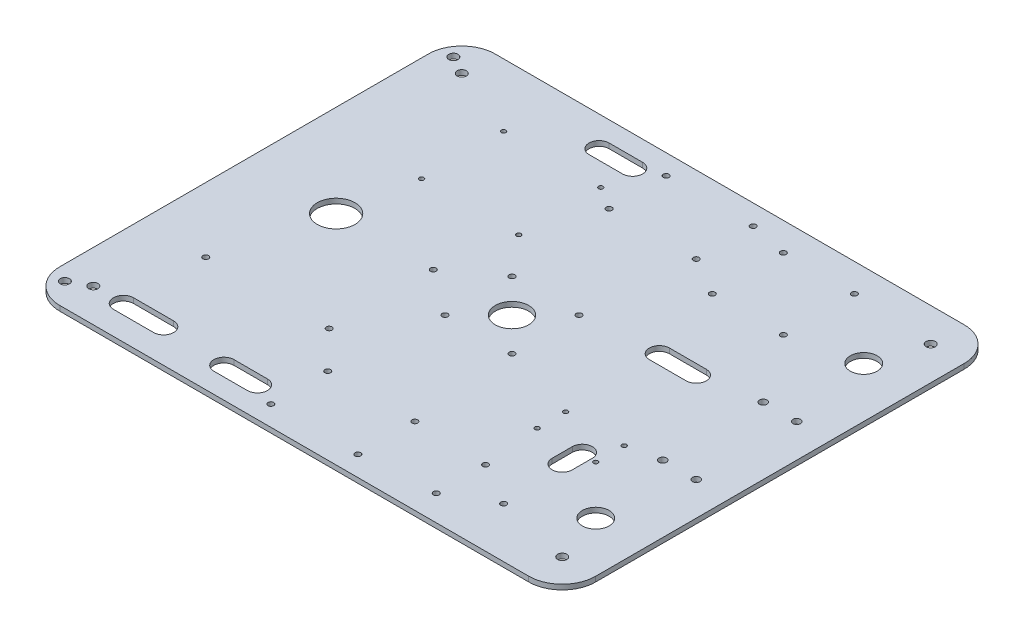
SolidWorks part; units mm, degrees
material "6061-T6 (SS)"
ref_plane "Front Plane" through (0, 0, 0) normal (0, 0, 1) x (1, 0, 0)
ref_plane "Top Plane" through (0, 0, 0) normal (0, 1, 0) x (1, 0, 0)
ref_plane "Right Plane" through (0, 0, 0) normal (1, 0, 0) x (0, 0, -1)
sketch "SK_Outline" plane through (0, 0, 0) normal (0, 1, 0) x (1, 0, 0)
  line L0 (160, -110) -> (160, 110)
  line L1 (140, 130) -> (-140, 130)
  line L2 (-160, 110) -> (-160, -110)
  line L3 (-140, -130) -> (140, -130)
  arc A0 (160, 110) -> (140, 130) centre (140, 110) ccw
  arc A1 (-140, 130) -> (-160, 110) centre (-140, 110) ccw
  arc A2 (-160, -110) -> (-140, -130) centre (-140, -110) ccw
  arc A3 (140, -130) -> (160, -110) centre (140, -110) ccw
extrude "Plate" add sketch "SK_Outline" along normal blind 3
sketch "SK_DeckPosts_M5" plane through (0, 0, 0) normal (0, 1, 0) x (1, 0, 0)
  circle A0 centre (140, -110) radius 2.75
  circle A1 centre (140, 110) radius 2.75
  circle A2 centre (-140, -110) radius 2.75
  circle A3 centre (-140, 110) radius 2.75
extrude "Cut_DeckPosts_M5" cut sketch "SK_DeckPosts_M5" against normal through all and the other way through all
sketch "SK_LidarRiser_M3" plane through (0, 0, 0) normal (0, 1, 0) x (1, 0, 0)
  circle A0 centre (20, -20) radius 1.7
  circle A1 centre (20, 20) radius 1.7
  circle A2 centre (-20, -20) radius 1.7
  circle A3 centre (-20, 20) radius 1.7
extrude "Cut_LidarRiser_M3" cut sketch "SK_LidarRiser_M3" against normal through all and the other way through all
sketch "SK_LidarCable_20" plane through (0, 0, 0) normal (0, 1, 0) x (1, 0, 0)
  circle A0 centre (0, 0) radius 10
extrude "Cut_LidarCable_20" cut sketch "SK_LidarCable_20" against normal through all and the other way through all
sketch "SK_Pi5_M2p5" plane through (0, 0, 0) normal (0, 1, 0) x (1, 0, 0)
  circle A0 centre (-97.5, 92.5) radius 1.35
  circle A1 centre (-97.5, 43.5) radius 1.35
  circle A2 centre (-39.5, 92.5) radius 1.35
  circle A3 centre (-39.5, 43.5) radius 1.35
extrude "Cut_Pi5_M2p5" cut sketch "SK_Pi5_M2p5" against normal through all and the other way through all
sketch "SK_ESP32Carrier_M3" plane through (0, 0, 0) normal (0, 1, 0) x (1, 0, 0)
  circle A0 centre (-121.35, -61.5) radius 1.7
  circle A1 centre (-47.65, -61.5) radius 1.7
extrude "Cut_ESP32Carrier_M3" cut sketch "SK_ESP32Carrier_M3" against normal through all and the other way through all
sketch "SK_EStop_22p5" plane through (0, 0, 0) normal (0, 1, 0) x (1, 0, 0)
  circle A0 centre (-105, 0) radius 11.25
extrude "Cut_EStop_22p5" cut sketch "SK_EStop_22p5" against normal through all and the other way through all
sketch "SK_Camera_M4" plane through (0, 0, 0) normal (0, 1, 0) x (1, 0, 0)
  circle A0 centre (120, -30) radius 2.25
  circle A1 centre (120, 30) radius 2.25
  circle A2 centre (140, -30) radius 2.25
  circle A3 centre (140, 30) radius 2.25
extrude "Cut_Camera_M4" cut sketch "SK_Camera_M4" against normal through all and the other way through all
sketch "SK_Lights_16" plane through (0, 0, 0) normal (0, 1, 0) x (1, 0, 0)
  circle A0 centre (130, -80) radius 8
  circle A1 centre (130, 80) radius 8
extrude "Cut_Lights_16" cut sketch "SK_Lights_16" against normal through all and the other way through all
sketch "SK_Handle_M5" plane through (0, 0, 0) normal (0, 1, 0) x (1, 0, 0)
  circle A0 centre (-151, -116) radius 2.75
  circle A1 centre (-151, 116) radius 2.75
extrude "Cut_Handle_M5" cut sketch "SK_Handle_M5" against normal through all and the other way through all
sketch "SK_PowerBlocks_M3" plane through (0, 0, 0) normal (0, 1, 0) x (1, 0, 0)
  circle A0 centre (-26, -84) radius 1.7
  circle A1 centre (-26, -118) radius 1.7
  circle A2 centre (26, -84) radius 1.7
  circle A3 centre (26, -118) radius 1.7
  circle A4 centre (-26, 84) radius 1.7
  circle A5 centre (-26, 118) radius 1.7
  circle A6 centre (26, 84) radius 1.7
  circle A7 centre (26, 118) radius 1.7
extrude "Cut_PowerBlocks_M3" cut sketch "SK_PowerBlocks_M3" against normal through all and the other way through all
sketch "SK_K2Relay_M2p5" plane through (0, 0, 0) normal (0, 1, 0) x (1, 0, 0)
  circle A0 centre (66, -34) radius 1.35
  circle A1 centre (66, -51) radius 1.35
  circle A2 centre (101, -34) radius 1.35
  circle A3 centre (101, -51) radius 1.35
extrude "Cut_K2Relay_M2p5" cut sketch "SK_K2Relay_M2p5" against normal through all and the other way through all
sketch "SK_LidarSplice_M3" plane through (0, 0, 0) normal (0, 1, 0) x (1, 0, 0)
  circle A0 centre (-47, 0) radius 1.7
extrude "Cut_LidarSplice_M3" cut sketch "SK_LidarSplice_M3" against normal through all and the other way through all
sketch "SK_MicArray_M3" plane through (0, 0, 0) normal (0, 1, 0) x (1, 0, 0)
  circle A0 centre (91.222, 70.795) radius 1.7
  circle A1 centre (48.791, 70.783) radius 1.7
  circle A2 centre (48.787, 113.213) radius 1.7
  circle A3 centre (91.218, 113.209) radius 1.7
extrude "Cut_MicArray_M3" cut sketch "SK_MicArray_M3" against normal through all and the other way through all
sketch "SK_Speaker_M3" plane through (0, 0, 0) normal (0, 1, 0) x (1, 0, 0)
  circle A0 centre (95, -100) radius 1.7
  circle A1 centre (69.506, -114.726) radius 1.7
  circle A2 centre (69.503, -85.276) radius 1.7
extrude "Cut_Speaker_M3" cut sketch "SK_Speaker_M3" against normal through all and the other way through all
sketch "SK_PassThroughs" plane through (0, 0, 0) normal (0, 1, 0) x (1, 0, 0)
  line L0 (-60, 118) -> (-40, 118)
  line L1 (-40, 106) -> (-60, 106)
  line L2 (-60, -106) -> (-40, -106)
  line L3 (-40, -118) -> (-60, -118)
  line L4 (-122, -104) -> (-98, -104)
  line L5 (-98, -116) -> (-122, -116)
  line L6 (64, 30) -> (86, 30)
  line L7 (86, 18) -> (64, 18)
  line L8 (98, -50) -> (98, -62)
  line L9 (86, -62) -> (86, -50)
  arc A0 (-40, 118) -> (-40, 106) centre (-40, 112) cw
  arc A1 (-60, 106) -> (-60, 118) centre (-60, 112) cw
  arc A2 (-40, -106) -> (-40, -118) centre (-40, -112) cw
  arc A3 (-60, -118) -> (-60, -106) centre (-60, -112) cw
  arc A4 (-98, -104) -> (-98, -116) centre (-98, -110) cw
  arc A5 (-122, -116) -> (-122, -104) centre (-122, -110) cw
  arc A6 (86, 30) -> (86, 18) centre (86, 24) cw
  arc A7 (64, 18) -> (64, 30) centre (64, 24) cw
  arc A8 (98, -62) -> (86, -62) centre (92, -62) cw
  arc A9 (86, -50) -> (98, -50) centre (92, -50) cw
extrude "Cut_PassThroughs" cut sketch "SK_PassThroughs" against normal through all and the other way through all
